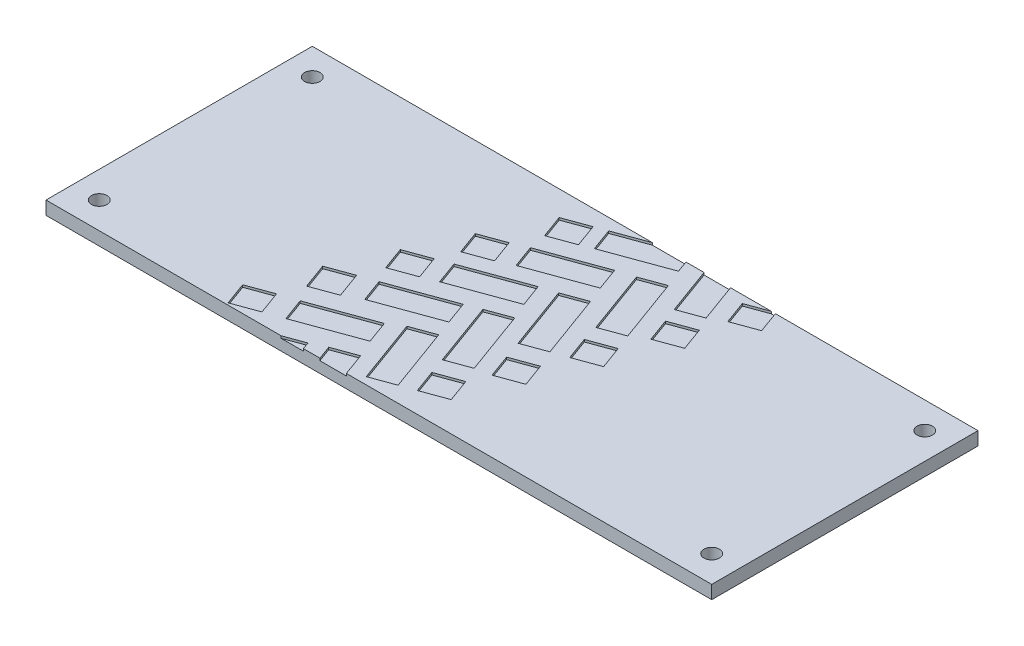
SolidWorks part; units mm, degrees
material "Acrylic (Medium-high impact)"
ref_plane "Front Plane" through (0, 0, 0) normal (0, 0, 1) x (1, 0, 0)
ref_plane "Top Plane" through (0, 0, 0) normal (0, 1, 0) x (1, 0, 0)
ref_plane "Right Plane" through (0, 0, 0) normal (1, 0, 0) x (0, 0, -1)
sketch "Sketch1" plane through (0, 0, 0) normal (0, 1, 0) x (1, 0, 0)
  line L1 (-54.3855, -28.8559) -> (95.6145, -28.8559)
  line L2 (-54.3855, -28.8559) -> (-54.3855, 31.1441)
  line L3 (-54.3855, 31.1441) -> (95.6145, 31.1441)
  line L4 (95.6145, -28.8559) -> (95.6145, 31.1441)
  dimension "D1" = 150
  dimension "D2" = 60
extrude "Boss-Extrude1" add sketch "Sketch1" along normal blind 3
sketch "Sketch2" plane through (0, 3, 0) normal (0, 1, 0) x (1, 0, 0)
  line L0 (95.6145, 31.1441) -> (-54.3855, 31.1441) construction
  line L1 (-54.3855, 31.1441) -> (-54.3855, -28.8559) construction
  line L2 (-54.3855, -28.8559) -> (95.6145, -28.8559) construction
  line L3 (95.6145, -28.8559) -> (95.6145, 31.1441) construction
  circle A0 centre (-48.3855, 25.1441) radius 1.75
  circle A1 centre (-48.3855, -22.8559) radius 1.75
  circle A2 centre (89.6145, -22.8559) radius 1.75
  circle A3 centre (89.6145, 25.1441) radius 1.75
  dimension "D1" = 3.5
  dimension "D2" = 6
  dimension "D3" = 6
  dimension "D4" = 6
  dimension "D5" = 6
extrude "Cut-Extrude1" cut sketch "Sketch2" against normal up to next
sketch "Sketch3" plane through (0, 3, 0) normal (0, 1, 0) x (1, 0, 0)
  line L0 (29.8883, 83.1009) -> (179.8883, 83.1009) construction
sketch "Sketch4" plane through (0, 3, 0) normal (0, 1, 0) x (1, 0, 0)
  line L0 (-4.7914, 1.3803) -> (-2.9043, -3.7892)
  line L1 (-2.9043, -3.7892) -> (2.6901, -1.747)
  line L2 (2.6901, -1.747) -> (0.8029, 3.4225)
  line L3 (0.8029, 3.4225) -> (-4.7914, 1.3803)
  line L4 (4.0722, 4.616) -> (17.9637, 9.6872)
  line L5 (17.9637, 9.6872) -> (19.815, 4.616)
  line L6 (19.815, 4.616) -> (5.9235, -0.4552)
  line L7 (5.9235, -0.4552) -> (4.0722, 4.616)
  line L8 (0.5376, 12.9427) -> (2.4248, 7.7732)
  line L9 (6.8551, 25.5346) -> (8.7423, 20.3651)
  line L10 (8.7423, 20.3651) -> (14.3366, 22.4074)
  line L11 (14.3366, 22.4074) -> (12.4495, 27.5769)
  line L12 (12.4495, 27.5769) -> (6.8551, 25.5346)
  line L13 (2.4248, 7.7732) -> (8.0192, 9.8154)
  line L14 (8.0192, 9.8154) -> (6.132, 14.9849)
  line L15 (6.132, 14.9849) -> (0.5376, 12.9427)
  line L16 (-10.3035, -10.5967) -> (-8.2225, -16.2973)
  line L17 (-8.2225, -16.2973) -> (-2.6281, -14.255)
  line L18 (-2.6281, -14.255) -> (-4.7092, -8.5544)
  line L19 (-4.7092, -8.5544) -> (-10.3035, -10.5967)
  line L20 (22.7347, -19.0268) -> (24.6218, -24.1964)
  line L21 (24.6218, -24.1964) -> (30.2162, -22.1541)
  line L22 (30.2162, -22.1541) -> (28.329, -16.9846)
  line L23 (28.329, -16.9846) -> (22.7347, -19.0268)
  line L24 (28.1596, -7.6173) -> (30.0468, -12.7868)
  line L25 (30.0468, -12.7868) -> (35.6411, -10.7445)
  line L26 (35.6411, -10.7445) -> (33.754, -5.575)
  line L27 (33.754, -5.575) -> (28.1596, -7.6173)
  line L28 (33.4705, 4.5812) -> (35.3576, -0.5883)
  line L29 (35.3576, -0.5883) -> (40.952, 1.454)
  line L30 (40.952, 1.454) -> (39.0648, 6.6235)
  line L31 (39.0648, 6.6235) -> (33.4705, 4.5812)
  line L32 (39.0332, 17.2988) -> (40.9204, 12.1292)
  line L33 (40.9204, 12.1292) -> (46.5148, 14.1715)
  line L34 (46.5148, 14.1715) -> (44.6276, 19.341)
  line L35 (44.6276, 19.341) -> (39.0332, 17.2988)
  line L36 (44.2601, 29.3975) -> (46.1473, 24.228)
  line L37 (46.1473, 24.228) -> (51.7417, 26.2702)
  line L38 (51.7417, 26.2702) -> (49.8545, 31.4397)
  line L39 (49.8545, 31.4397) -> (44.2601, 29.3975)
  line L40 (-15.6935, -23.2381) -> (-13.8063, -28.4076)
  line L41 (-13.8063, -28.4076) -> (-8.2119, -26.3653)
  line L42 (-8.2119, -26.3653) -> (-10.0991, -21.1958)
  line L43 (-10.0991, -21.1958) -> (-15.6935, -23.2381)
  line L44 (-0.9303, -7.2729) -> (12.9612, -2.2017)
  line L45 (12.9612, -2.2017) -> (14.8124, -7.2729)
  line L46 (14.8124, -7.2729) -> (0.9209, -12.3441)
  line L47 (0.9209, -12.3441) -> (-0.9303, -7.2729)
  line L48 (-6.0745, -19.8913) -> (7.817, -14.8202)
  line L49 (7.817, -14.8202) -> (9.6682, -19.8913)
  line L50 (9.6682, -19.8913) -> (-4.2233, -24.9625)
  line L51 (-4.2233, -24.9625) -> (-6.0745, -19.8913)
  line L52 (9.4974, 16.4097) -> (23.3889, 21.4809)
  line L53 (23.3889, 21.4809) -> (25.2401, 16.4097)
  line L54 (25.2401, 16.4097) -> (11.3486, 11.3386)
  line L55 (11.3486, 11.3386) -> (9.4974, 16.4097)
  line L56 (15.0297, 28.5145) -> (28.9212, 33.5856)
  line L57 (28.9212, 33.5856) -> (30.7725, 28.5145)
  line L58 (30.7725, 28.5145) -> (16.881, 23.4433)
  line L59 (16.881, 23.4433) -> (15.0297, 28.5145)
  line L60 (-10.8626, -32.3129) -> (3.0289, -27.2417)
  line L61 (3.0289, -27.2417) -> (4.8802, -32.3129)
  line L62 (4.8802, -32.3129) -> (-9.0113, -37.384)
  line L63 (-9.0113, -37.384) -> (-10.8626, -32.3129)
  line L64 (16.1615, -27.2417) -> (21.4213, -25.3216)
  line L65 (21.4213, -25.3216) -> (16.1615, -10.9134)
  line L66 (16.1615, -10.9134) -> (10.9017, -12.8335)
  line L67 (10.9017, -12.8335) -> (16.1615, -27.2417)
  line L68 (11.4529, -40.1375) -> (16.7127, -38.2174)
  line L69 (16.7127, -38.2174) -> (11.4529, -23.8092)
  line L70 (11.4529, -23.8092) -> (6.1931, -25.7293)
  line L71 (6.1931, -25.7293) -> (11.4529, -40.1375)
  line L72 (21.4327, -15.3745) -> (26.6925, -13.4544)
  line L73 (26.6925, -13.4544) -> (21.4327, 0.9538)
  line L74 (21.4327, 0.9538) -> (16.173, -0.9663)
  line L75 (16.173, -0.9663) -> (21.4327, -15.3745)
  line L76 (26.7487, -3.6296) -> (32.0085, -1.7095)
  line L77 (32.0085, -1.7095) -> (26.7487, 12.6987)
  line L78 (26.7487, 12.6987) -> (21.4889, 10.7786)
  line L79 (21.4889, 10.7786) -> (26.7487, -3.6296)
  line L80 (32.423, 8.2327) -> (37.6828, 10.1528)
  line L81 (37.6828, 10.1528) -> (32.423, 24.561)
  line L82 (32.423, 24.561) -> (27.1632, 22.6409)
  line L83 (27.1632, 22.6409) -> (32.423, 8.2327)
  line L84 (37.7544, 20.5583) -> (43.0141, 22.4784)
  line L85 (43.0141, 22.4784) -> (37.7544, 36.8866)
  line L86 (37.7544, 36.8866) -> (32.4946, 34.9665)
  line L87 (32.4946, 34.9665) -> (37.7544, 20.5583)
  point P68 (24.6218, -39.2419)
  point P69 (16.881, -27.2417)
  point P70 (16.1615, -27.2417)
extrude "Cut-Extrude2" cut sketch "Sketch4" against normal blind 0.5
